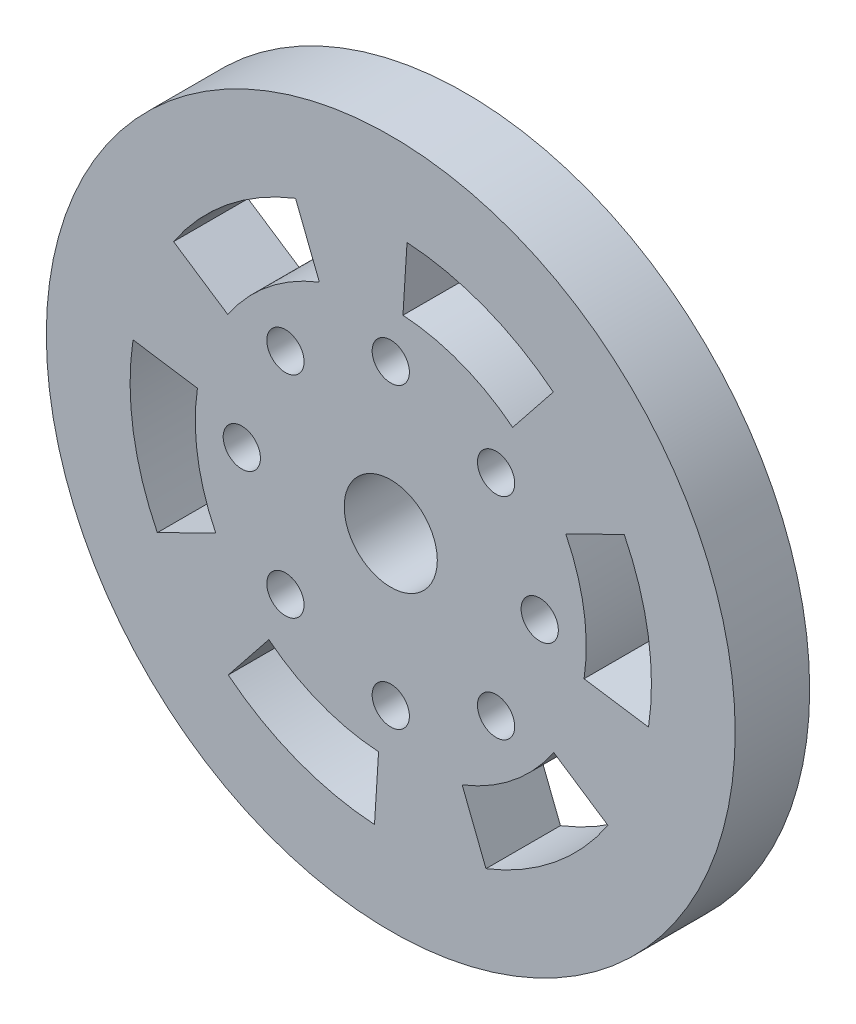
SolidWorks part; units mm, degrees
ref_plane "Plan de face" through (0, 0, 0) normal (0, 0, 1) x (1, 0, 0)
ref_plane "Plan de dessus" through (0, 0, 0) normal (0, 1, 0) x (1, 0, 0)
ref_plane "Plan de droite" through (0, 0, 0) normal (1, 0, 0) x (0, 0, -1)
sketch "Esquisse1" plane through (0, 0, 0) normal (0, 0, 1) x (1, 0, 0)
  circle A0 centre (0, 0) radius 22.2
  dimension "D1" = 44.4
extrude "Boss.-Extru.1" add sketch "Esquisse1" along normal blind 4.8
sketch "Esquisse2" plane through (0, 0, 4.8) normal (0, 0, 1) x (1, 0, 0)
  line L0 (-13.997, 9.2911) -> (-10.4977, 6.9683)
  line L1 (-6.1365, 15.6392) -> (-4.6024, 11.7294)
  line L2 (1.0478, 16.7673) -> (0.7859, 12.5755)
  line L3 (10.4757, 13.134) -> (7.8567, 9.8505)
  line L4 (15.0448, 7.4762) -> (11.2836, 5.6071)
  line L5 (16.6122, -2.5052) -> (12.4591, -1.8789)
  line L6 (13.997, -9.2911) -> (10.4977, -6.9683)
  line L7 (6.1365, -15.6392) -> (4.6024, -11.7294)
  line L8 (-1.0478, -16.7673) -> (-0.7859, -12.5755)
  line L9 (-10.4757, -13.134) -> (-7.8567, -9.8505)
  line L10 (-15.0448, -7.4762) -> (-11.2836, -5.6071)
  line L11 (-16.6122, 2.5052) -> (-12.4591, 1.8789)
  arc A0 (-6.1365, 15.6392) -> (-13.997, 9.2911) centre (0, 0) ccw
  arc A1 (-4.6024, 11.7294) -> (-10.4977, 6.9683) centre (0, 0) ccw
  arc A2 (7.8567, 9.8505) -> (0.7859, 12.5755) centre (0, 0) ccw
  arc A3 (10.4757, 13.134) -> (1.0478, 16.7673) centre (0, 0) ccw
  arc A4 (12.4591, -1.8789) -> (11.2836, 5.6071) centre (0, 0) ccw
  arc A5 (16.6122, -2.5052) -> (15.0448, 7.4762) centre (0, 0) ccw
  arc A6 (4.6024, -11.7294) -> (10.4977, -6.9683) centre (0, 0) ccw
  arc A7 (6.1365, -15.6392) -> (13.997, -9.2911) centre (0, 0) ccw
  arc A8 (-7.8567, -9.8505) -> (-0.7859, -12.5755) centre (0, 0) ccw
  arc A9 (-10.4757, -13.134) -> (-1.0478, -16.7673) centre (0, 0) ccw
  arc A10 (-12.4591, 1.8789) -> (-11.2836, -5.6071) centre (0, 0) ccw
  arc A11 (-16.6122, 2.5052) -> (-15.0448, -7.4762) centre (0, 0) ccw
  circle A12 centre (0, 0) radius 3
  circle A13 centre (9.6, 0) radius 1.2
  circle A14 centre (6.7882, -6.7882) radius 1.2
  circle A15 centre (0, -9.6) radius 1.2
  circle A16 centre (-6.7882, -6.7882) radius 1.2
  circle A17 centre (-9.6, 0) radius 1.2
  circle A18 centre (-6.7882, 6.7882) radius 1.2
  circle A19 centre (0, 9.6) radius 1.2
  circle A20 centre (6.7882, 6.7882) radius 1.2
  point P29 (0, 0)
  point P47 (0, 0)
  dimension "D1" = 35
  dimension "D2" = 4.2
  dimension "D5" = 6
  dimension "D6" = 2.4
  dimension "D4" = 60
  dimension "D7" = 9.6
  dimension "D9" = 9.6
  dimension "D3" = 6
  dimension "D8" = 8
extrude "Enlèv. mat.-Extru.1" cut sketch "Esquisse2" against normal through all
